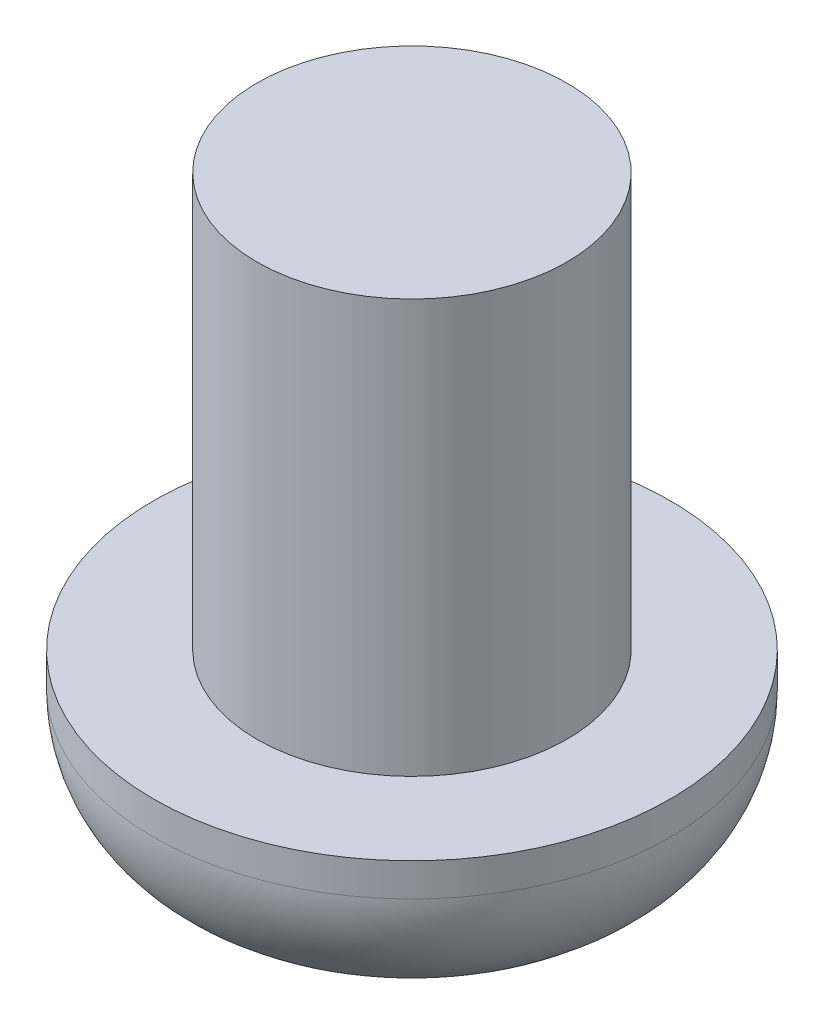
SolidWorks part; units mm, degrees
ref_plane "Front Plane" through (0, 0, 0) normal (0, 0, 1) x (1, 0, 0)
ref_plane "Top Plane" through (0, 0, 0) normal (0, 1, 0) x (1, 0, 0)
ref_plane "Right Plane" through (0, 0, 0) normal (1, 0, 0) x (0, 0, -1)
sketch "Sketch1" plane through (0, 0, 0) normal (0, 1, 0) x (1, 0, 0)
  circle A0 centre (0, 0) radius 2.3812
  circle A1 centre (0, 0) radius 3.9688
  dimension "D1" = 7.9375
  dimension "D2" = 4.7625
extrude "Boss-Extrude2" add sketch "Sketch1" along normal blind 2.54
sketch "Sketch2" plane through (0, 2.54, 0) normal (0, 1, 0) x (1, 0, 0)
  circle A0 centre (0, 0) radius 2.3812
extrude "Boss-Extrude3" add sketch "Sketch2" along normal blind 6.35 and the other way blind 2.54
sketch "Sketch3" plane through (0, 0, 0) normal (0, -1, 0) x (-1, 0, 0)
  circle A0 centre (0, 0) radius 1.5875
  dimension "D1" = 3.175
extrude "Cut-Extrude1" cut sketch "Sketch3" against normal blind 3.175
fillet "Fillet1" radius 2.032 1 edges at (0, 0, 3.9688)
fillet "Fillet2" radius 0.508 1 edges at (0, 0, -1.5875)
